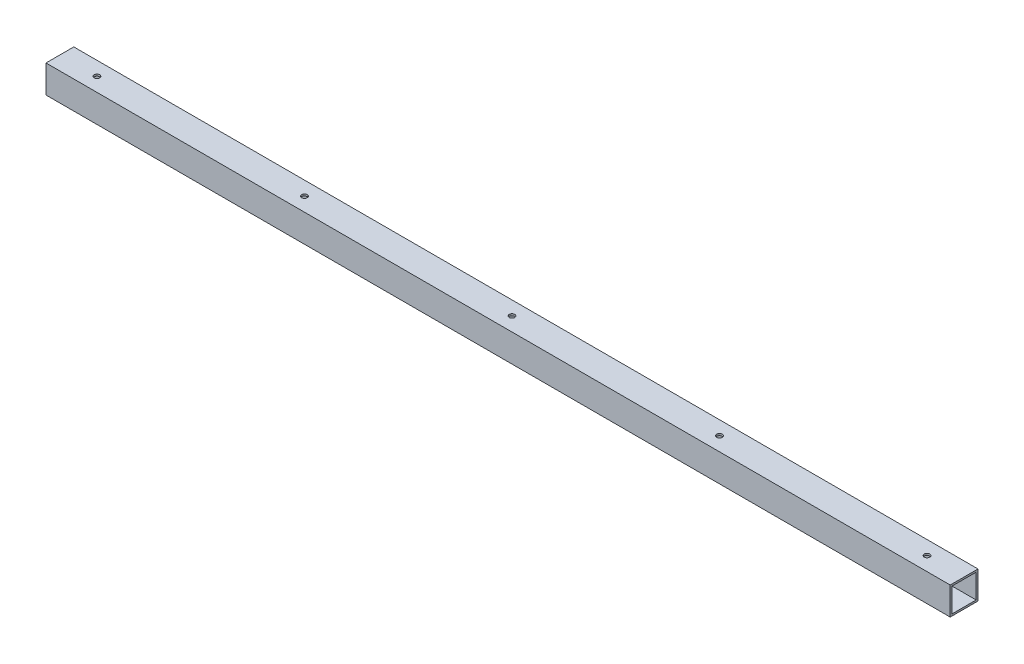
SolidWorks part; units mm, degrees
material "Hexcel AS4C (3000 丝)"
ref_plane "前视基准面" through (0, 0, 0) normal (0, 0, 1) x (1, 0, 0)
ref_plane "上视基准面" through (0, 0, 0) normal (0, 1, 0) x (1, 0, 0)
ref_plane "右视基准面" through (0, 0, 0) normal (1, 0, 0) x (0, 0, -1)
sketch "草图1" plane through (0, 0, 0) normal (0, 1, 0) x (1, 0, 0)
  line L0 (-244, 0) -> (244, 0)
  dimension "D1" = 488
other "矩形管 方铝管15X15X1(1)"
ref_plane "基准面1" through (-244, 0, 0) normal (1, 0, 0) x (0, 0, -1)
sketch "草图21" plane through (-244, 0, 0) normal (1, 0, 0) x (0, 0, -1)
  line L0 (-6.5, 6.5) -> (6.5, 6.5)
  line L1 (-7.5, 7.5) -> (7.5, 7.5)
  line L2 (-7.5, 7.5) -> (-7.5, -7.5)
  line L3 (-7.5, -7.5) -> (7.5, -7.5)
  line L4 (7.5, 7.5) -> (7.5, -7.5)
  line L5 (-7.5, 7.5) -> (7.5, -7.5) construction
  line L6 (-7.5, -7.5) -> (7.5, 7.5) construction
  line L7 (6.5, 6.5) -> (6.5, -6.5)
  line L8 (-6.5, -6.5) -> (6.5, -6.5)
  line L9 (-6.5, 6.5) -> (-6.5, -6.5)
  point P0 (0, 0)
  point P10 (0, 0)
  dimension "D1" = 15
  dimension "D2" = 1
sketch "草图3" plane through (0, -7.5, 0) normal (0, 1, 0) x (1, 0, 0)
  line L0 (244, -7.5) -> (244, 7.5) construction
  line L1 (-244, -7.5) -> (-244, 7.5) construction
  circle A0 centre (-224, 0) radius 1.5
  circle A1 centre (-112, 0) radius 1.5
  circle A2 centre (0, 0) radius 1.5
  circle A3 centre (112, 0) radius 1.5
  circle A4 centre (224, 0) radius 1.5
  dimension "D1" = 3
  dimension "D2" = 4
  dimension "D3" = 3
  dimension "D4" = 20
  dimension "D7" = 20
extrude "切除-拉伸1" cut sketch "草图3" along normal through all
